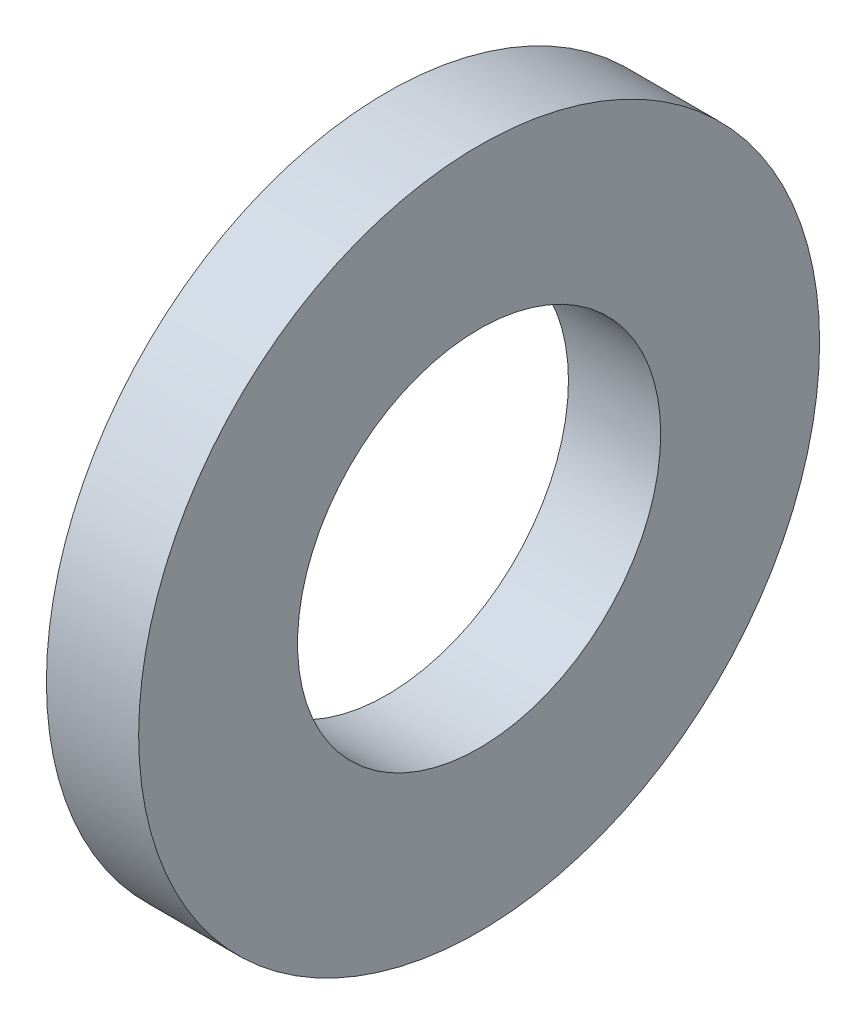
SolidWorks part; units mm, degrees
material "6061 Alloy"
ref_plane "XY" through (0, 0, 0) normal (1, 0, 0) x (0, 1, 0)
ref_plane "XZ" through (0, 0, 0) normal (0, 0, 1) x (0, 1, 0)
ref_plane "YZ" through (0, 0, 0) normal (0, 1, 0) x (-1, 0, 0)
sketch "Sketch1" plane through (0, 0, 0) normal (1, 0, 0) x (0, 1, 0)
  circle A0 centre (0, 0) radius 1.6
  circle A1 centre (0, 0) radius 3
  dimension "D1" = 3.2
  dimension "D2" = 6
extrude "Boss-Extrude1" add sketch "Sketch1" along normal blind 0.8128
